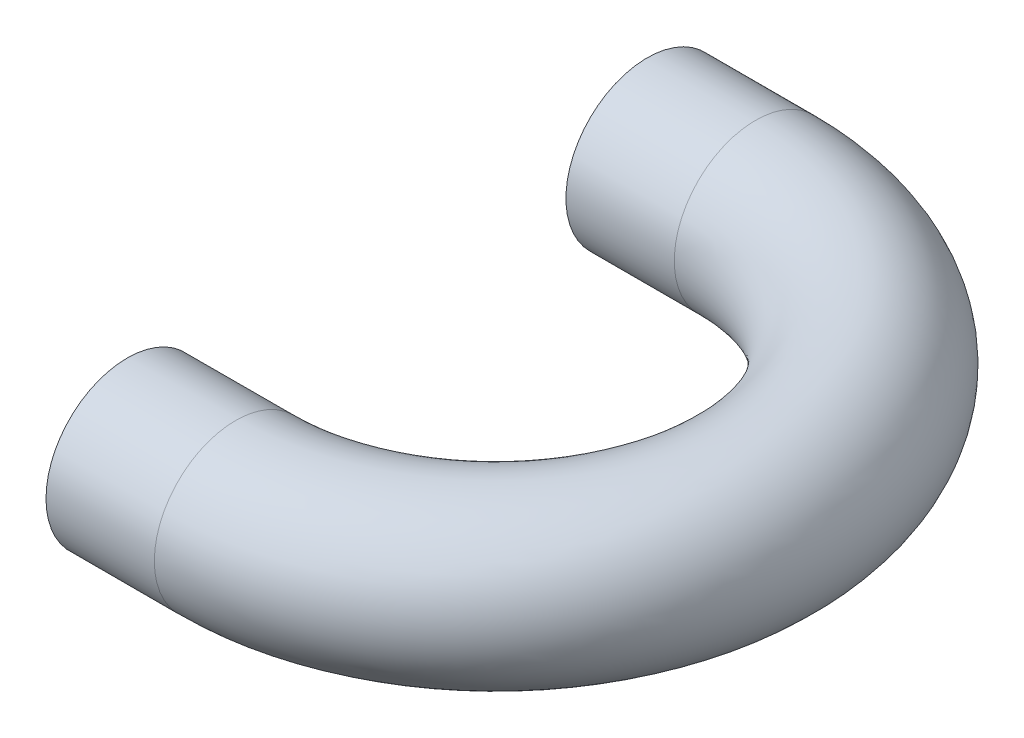
SolidWorks part; units mm, degrees
ref_plane "Front Plane" through (0, 0, 0) normal (0, 0, 1) x (1, 0, 0)
ref_plane "Top Plane" through (0, 0, 0) normal (0, 1, 0) x (1, 0, 0)
ref_plane "Right Plane" through (0, 0, 0) normal (1, 0, 0) x (0, 0, -1)
sketch "Sketch1" plane through (0, 0, 0) normal (1, 0, 0) x (0, 0, -1)
  circle A0 centre (0, 0) radius 3.175
  circle A1 centre (0, 0) radius 4.7625
  circle A2 centre (30.48, 0) radius 3.175
  circle A3 centre (30.48, 0) radius 4.7625
  dimension "D1" = 6.35
  dimension "D2" = 9.525
extrude "Boss-Extrude1" add sketch "Sketch1" along normal blind 6.35
sketch "Sketch2" plane through (6.35, 0, 0) normal (1, 0, 0) x (0, 0, -1)
  line L0 (15.24, 0) -> (15.24, 26.6878) construction
  circle A1 centre (0, 0) radius 4.7625 construction
  circle A3 centre (0, 0) radius 4.7625
  circle A4 centre (0, 0) radius 3.175 construction
  circle A5 centre (0, 0) radius 3.175
  dimension "D1" = 15.24
revolve "Revolve1" add sketch "Sketch2" angle 180 about L0
